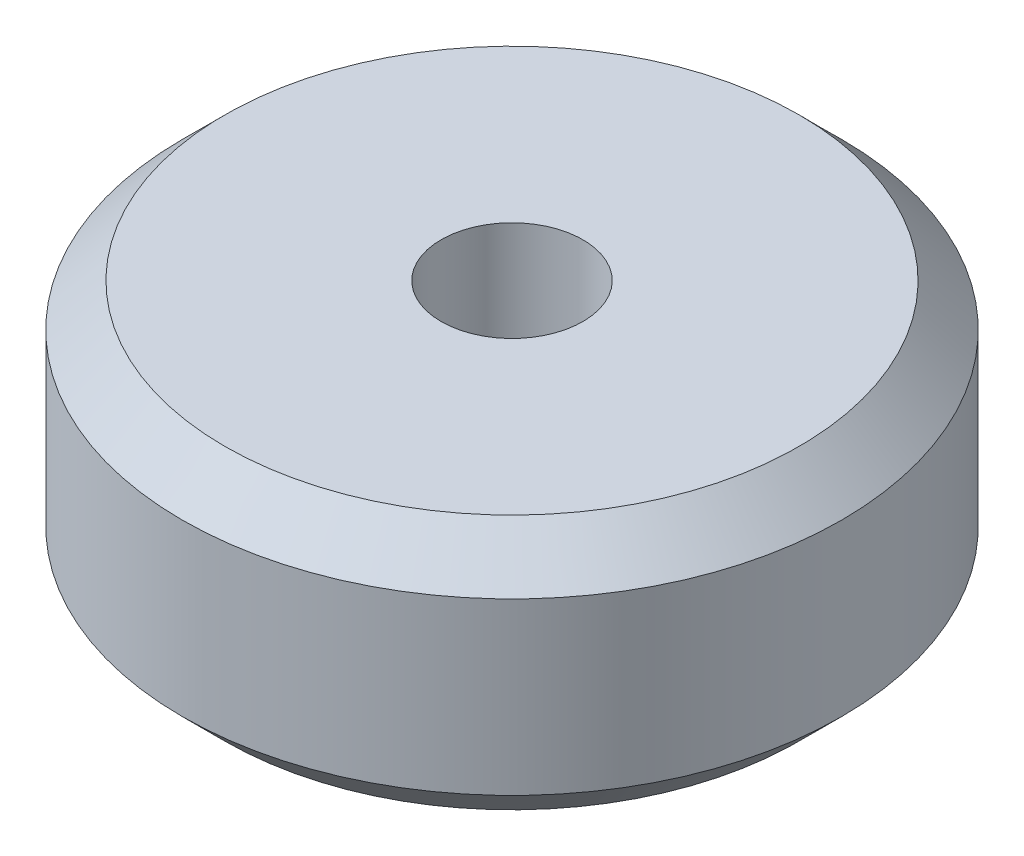
SolidWorks part; units mm, degrees
material "Rubber"
ref_plane "Front Plane" through (0, 0, 0) normal (0, 0, 1) x (1, 0, 0)
ref_plane "Top Plane" through (0, 0, 0) normal (0, 1, 0) x (1, 0, 0)
ref_plane "Right Plane" through (0, 0, 0) normal (1, 0, 0) x (0, 0, -1)
sketch "Sketch1" plane through (0, 0, 0) normal (0, 1, 0) x (1, 0, 0)
  circle A0 centre (0, 0) radius 2.5
  circle A1 centre (0, 0) radius 11.625
  dimension "D1" = 5
  dimension "D2" = 23.25
extrude "Boss-Extrude1" add sketch "Sketch1" along normal blind 9
chamfer "Chamfer1" distance 1.5 angle 45 2 edges at (0, 0, 11.625) (0, 9, 11.625)
